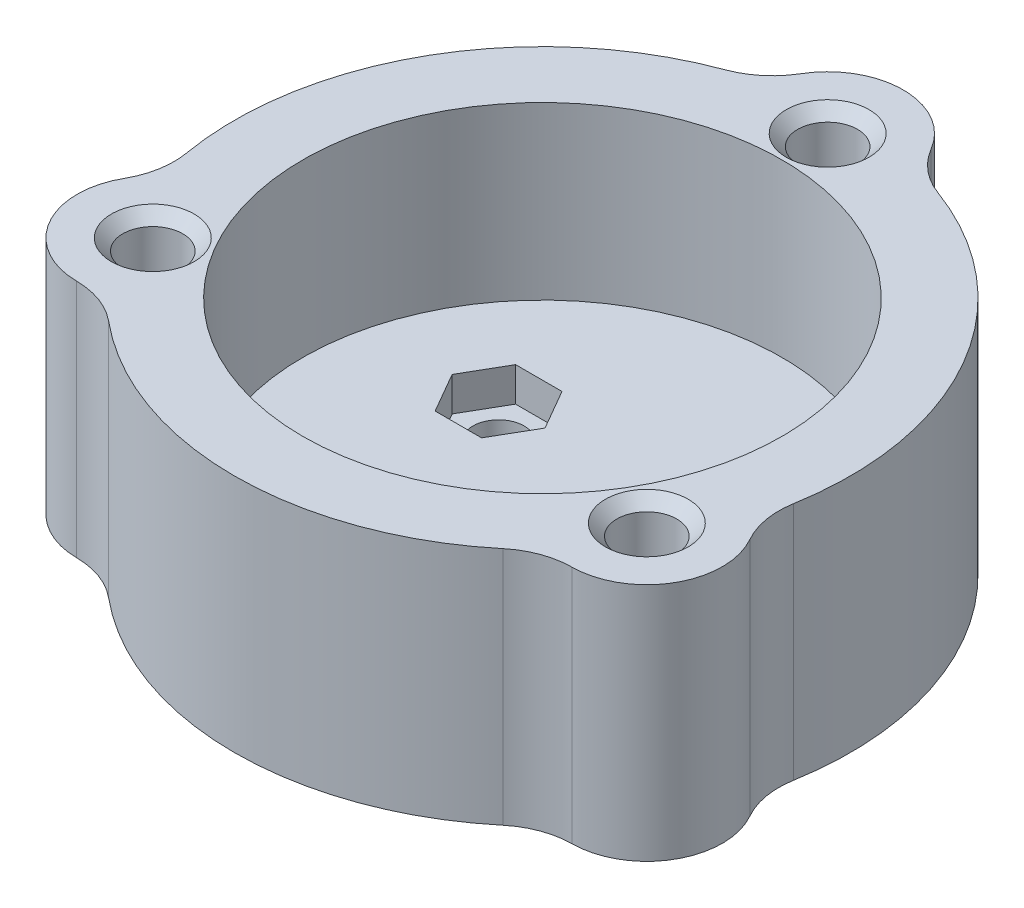
SolidWorks part; units mm, degrees
ref_plane "Спереди" through (0, 0, 0) normal (0, 0, 1) x (1, 0, 0)
ref_plane "Сверху" through (0, 0, 0) normal (0, 1, 0) x (1, 0, 0)
ref_plane "Справа" through (0, 0, 0) normal (1, 0, 0) x (0, 0, -1)
sketch "Эскиз1" plane through (0, 0, 0) normal (0, 1, 0) x (1, 0, 0)
  circle A0 centre (0, 0) radius 25 construction
  circle A1 centre (0, 25) radius 2.625
  circle A3 centre (0, 25) radius 6.625
  circle A4 centre (0, 0) radius 21
  circle A5 centre (0, 0) radius 27
  circle A6 centre (21.6506, -12.5) radius 6.625
  circle A7 centre (21.6506, -12.5) radius 2.625
  circle A8 centre (-21.6506, -12.5) radius 6.625
  circle A9 centre (-21.6506, -12.5) radius 2.625
  dimension "D1" = 50
  dimension "D2" = 5.25
  dimension "D3" = 4
  dimension "D5" = 4
  dimension "D4" = 2
  dimension "D6" = 3
extrude "Бобышка-Вытянуть1" add sketch "Эскиз1" along normal blind 15 contours A5 A3 A1 | A3 A5 A1 A4 | A6 A5 A3 A4 | A8 A4 A3 A5 | A7 A5 A6 A4 | A7 A5 A6 | A8 A5 A6 A4 | A9 A5 A8 | A9 A5 A8 A4
sketch "Эскиз2" plane through (0, 0, 0) normal (0, -1, 0) x (1, 0, 0)
  arc A27 (25.9493, 7.4589) -> (19.4343, 18.7433) centre (21.6506, 12.5) ccw
  arc A28 (6.515, -26.2022) -> (25.9493, 7.4589) centre (0, 0) ccw
  arc A29 (-6.515, -26.2022) -> (6.515, -26.2022) centre (0, -25) ccw
  arc A30 (-25.9493, 7.4589) -> (-6.515, -26.2022) centre (0, 0) ccw
  arc A31 (-19.4343, 18.7433) -> (-25.9493, 7.4589) centre (-21.6506, 12.5) ccw
  arc A32 (19.4343, 18.7433) -> (-19.4343, 18.7433) centre (0, 0) ccw
  arc A33 (25.9493, 7.4589) -> (19.4343, 18.7433) centre (21.6506, 12.5) ccw
  arc A34 (6.515, -26.2022) -> (25.9493, 7.4589) centre (0, 0) ccw
  arc A35 (-6.515, -26.2022) -> (6.515, -26.2022) centre (0, -25) ccw
  arc A36 (-25.9493, 7.4589) -> (-6.515, -26.2022) centre (0, 0) ccw
  arc A37 (-19.4343, 18.7433) -> (-25.9493, 7.4589) centre (-21.6506, 12.5) ccw
  arc A38 (19.4343, 18.7433) -> (-19.4343, 18.7433) centre (0, 0) ccw
  dimension "D1" = 0
extrude "Бобышка-Вытянуть2" add sketch "Эскиз2" along normal blind 6
fillet "Скругление1" radius 7 6 edges at (6.515, 4.5, -26.2022) (-6.515, 4.5, -26.2022) (-25.9493, 4.5, 7.4589) (-19.4343, 4.5, 18.7433) (19.4343, 4.5, 18.7433) (25.9493, 4.5, 7.4589)
chamfer "Фаска1" distance 1 angle 45 3 edges at (0, 15, -22.375) (21.6506, 15, 15.125) (-21.6506, 15, 15.125)
sketch "Эскиз3" plane through (0, -6, 0) normal (0, -1, 0) x (1, 0, 0)
  circle A0 centre (0, 0) radius 10.5 construction
  circle A1 centre (0, 10.5) radius 2.25
  circle A2 centre (9.0933, -5.25) radius 2.25
  circle A3 centre (-9.0933, -5.25) radius 2.25
  dimension "D1" = 21
  dimension "D2" = 4.5
  dimension "D3" = 3
extrude "Вырез-Вытянуть1" cut sketch "Эскиз3" against normal through all
sketch "Эскиз4" plane through (0, 0, 0) normal (0, 1, 0) x (1, 0, 0)
  line L0 (-4.0703, -10.5) -> (-2.0352, -14.025)
  line L1 (11.1284, 1.725) -> (13.1636, 5.25)
  line L2 (13.1636, 5.25) -> (11.1284, 8.775)
  line L3 (11.1284, 8.775) -> (7.0581, 8.775)
  line L4 (7.0581, 8.775) -> (5.0229, 5.25)
  line L5 (5.0229, 5.25) -> (7.0581, 1.725)
  line L6 (7.0581, 1.725) -> (11.1284, 1.725)
  line L7 (-2.0352, -14.025) -> (2.0352, -14.025)
  line L8 (2.0352, -14.025) -> (4.0703, -10.5)
  line L9 (4.0703, -10.5) -> (2.0352, -6.975)
  line L10 (2.0352, -6.975) -> (-2.0352, -6.975)
  line L11 (-2.0352, -6.975) -> (-4.0703, -10.5)
  line L12 (-7.0581, 8.775) -> (-11.1284, 8.775)
  line L13 (-11.1284, 8.775) -> (-13.1636, 5.25)
  line L14 (-13.1636, 5.25) -> (-11.1284, 1.725)
  line L15 (-11.1284, 1.725) -> (-7.0581, 1.725)
  line L16 (-7.0581, 1.725) -> (-5.0229, 5.25)
  line L17 (-5.0229, 5.25) -> (-7.0581, 8.775)
  circle A0 centre (9.0933, 5.25) radius 3.525 construction
  circle A1 centre (0, -10.5) radius 3.525 construction
  circle A2 centre (-9.0933, 5.25) radius 3.525 construction
  circle A3 centre (0, -10.5) radius 2.25 construction
  dimension "D1" = 7.05
  dimension "D2" = 3
extrude "Вырез-Вытянуть2" cut sketch "Эскиз4" against normal blind 3
equation "\"motor_diameter\"= 30"
equation "\"mm_diameter\"= IIF ( \"motor_diameter\" < 34 , 41 , \"motor_diameter\" + 8 )"
equation "\"upper_shafts_diameter\"= 5"
equation "\"upper_shats_length\"= 180"
equation "\"upper_bearing_d1\"= 10"
equation "\"upper_bearing_d2\"= 5"
equation "\"upper_bearing_h\"= 15"
equation "\"lower_shafts_diameter\"= 5"
equation "\"lower_shafts_length\"= 180"
equation "\"lower_bearing_d1\"= 10"
equation "\"lower_bearing_d2\"= 5"
equation "\"lower_bearing_h\"= 15"
equation "\"print_offset\"= 0.5"
equation "\"bh_screws_d\"= 2"
equation "\"bh_screws_h\"= 20"
equation "\"bh_screws_hh_d\"= 3.4"
equation "\"bh_screws_hh_h\"= 2"
equation "\"bh_nut_d\"= 3.8"
equation "\"bh_nut_h\"= 2"
equation "\"motor_screws_d\"= 3"
equation "\"motor_screws_h\"= 16"
equation "\"motor_screws_hh_d\"= 5.5"
equation "\"motor_screws_hh_h\"= 3"
equation "\"plate_hole_distance\"= 25.4"
equation "\"plate_screws_d\"= 6.5"
equation "\"shafts_diameter\"= IIF ( \"mm_diameter\" < 42 , 42 + 8 , \"mm_diameter\" + 8 )"
equation "\"central_hole_diameter\"= 8"
equation "\"bh_thikness\"= 4"
equation "\"D1@Эскиз1\"=\"shafts_diameter\""
equation "\"D2@Эскиз1\" = \"lower_shafts_diameter\" + \"print_offset\" / 2"
equation "\"D3@Эскиз1\"=\"bh_thikness\""
equation "\"D5@Эскиз1\"=\"D3@Эскиз1\""
equation "\"D1@Бобышка-Вытянуть1\"= \"lower_bearing_h\""
equation "\"D1@Бобышка-Вытянуть2\"=6"
equation "\"D4@Эскиз1\"=\"D3@Эскиз1\"/2"
equation "\"ends_screws_d\"= 4"
equation "\"ends_screws_h\"= 16"
equation "\"ends_screws_hh_d\"= 6.7"
equation "\"ends_screws_hh_h\"= 4.1"
equation "\"ends_nut_d\"= 6.8"
equation "\"ends_nut_h\"= 3"
equation "\"D2@Эскиз3\"=\"ends_screws_d\"+\"print_offset\""
equation "\"D1@Эскиз4\"=\"ends_nut_d\"+\"print_offset\"/2"
equation "\"D1@Вырез-Вытянуть2\"=\"ends_nut_h\""
